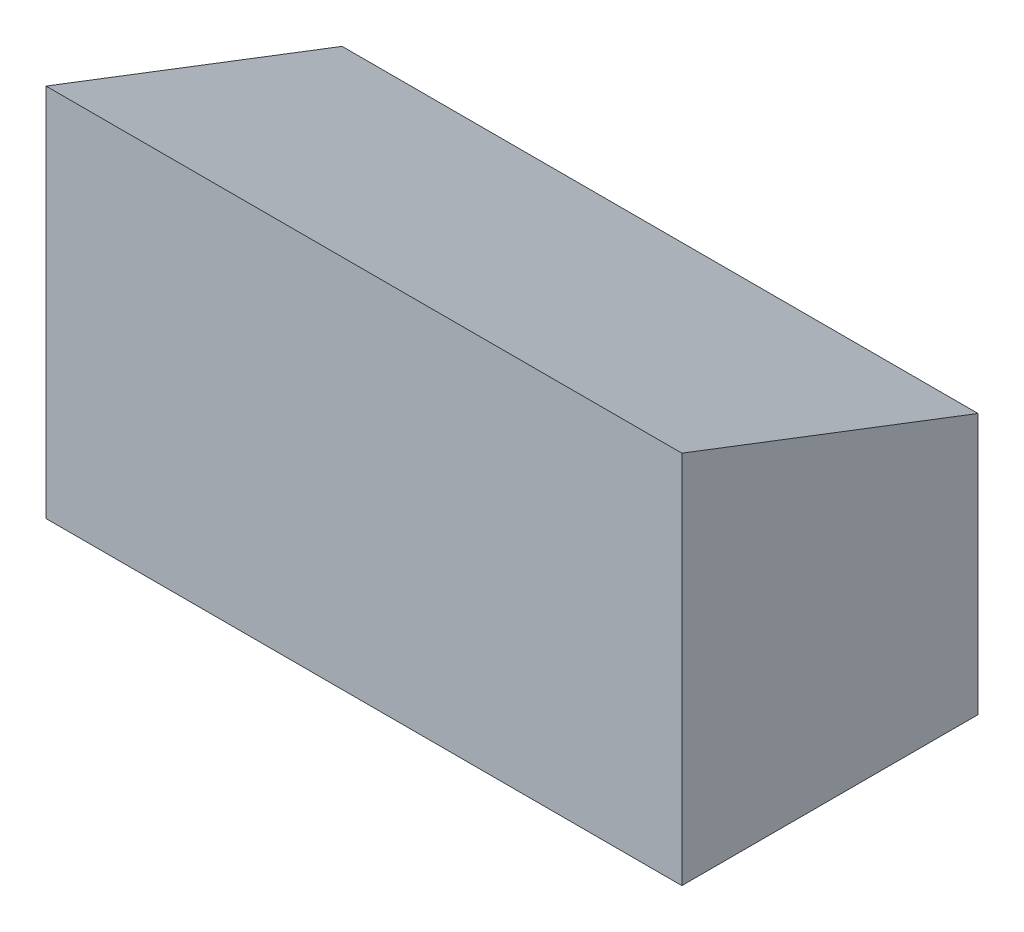
SolidWorks part; units mm, degrees
ref_plane "Front Plane" through (0, 0, 0) normal (0, 0, 1) x (1, 0, 0)
ref_plane "Top Plane" through (0, 0, 0) normal (0, 1, 0) x (1, 0, 0)
ref_plane "Right Plane" through (0, 0, 0) normal (1, 0, 0) x (0, 0, -1)
sketch "Sketch1" plane through (0, 0, 0) normal (1, 0, 0) x (0, 0, -1)
  line L0 (0, 0) -> (0, 29.9486)
  line L1 (0, 29.9486) -> (-34, 43)
  line L2 (-34, 43) -> (-34, 0)
  line L3 (-34, 0) -> (0, 0)
  dimension "D1" = 34
  dimension "D2" = 43
  dimension "D3" = 29.9486
  dimension "D4" = 69
extrude "Boss-Extrude1" add sketch "Sketch1" along normal mid plane 73
